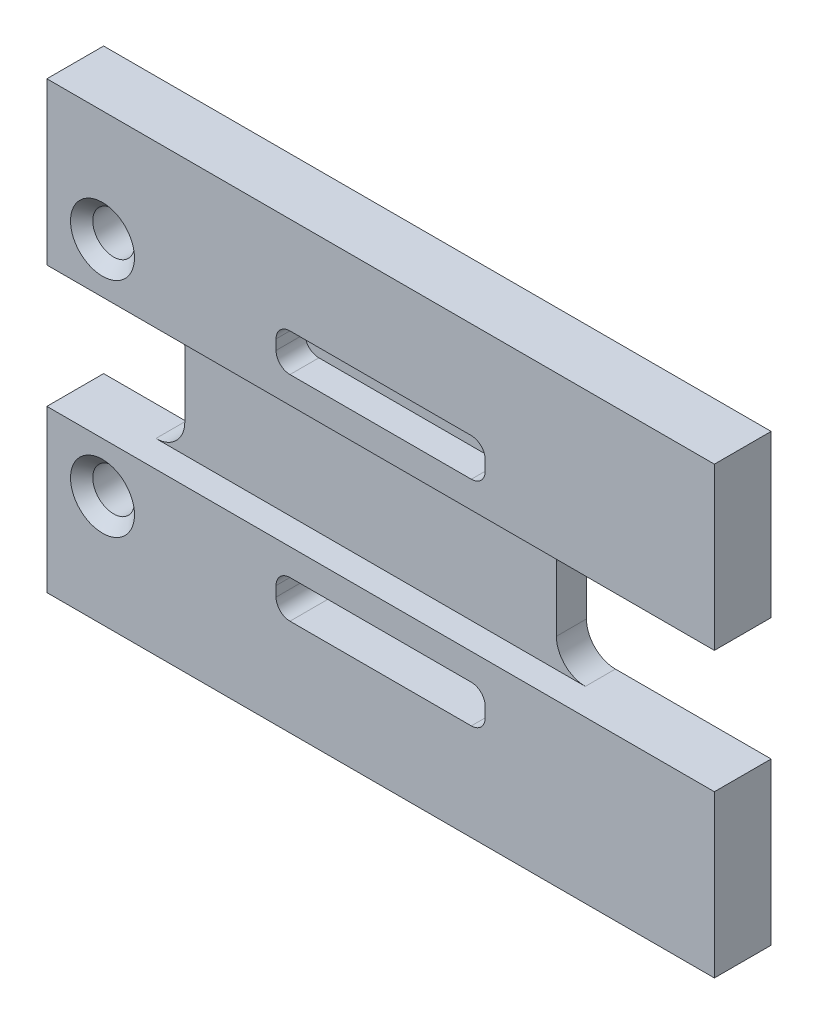
SolidWorks part; units mm, degrees
ref_plane "Front Plane" through (0, 0, 0) normal (1, 0, 0) x (0, 1, 0)
ref_plane "Top Plane" through (0, 0, 0) normal (0, 0, 1) x (0, 1, 0)
ref_plane "Right Plane" through (0, 0, 0) normal (0, 1, 0) x (-1, 0, 0)
sketch "Sketch1" plane through (0, 0, 0) normal (0, 0, 1) x (0, 1, 0)
  line L0 (-25.4, 38.1) -> (25.4, -38.1) construction
  line L1 (-25.4, 38.1) -> (25.4, 38.1)
  line L2 (-25.4, 38.1) -> (-25.4, -38.1)
  line L3 (-25.4, -38.1) -> (25.4, -38.1)
  line L4 (25.4, 38.1) -> (25.4, -38.1)
  line L5 (25.4, 38.1) -> (-25.4, -38.1) construction
  dimension "D1" = 50.8
  dimension "D2" = 76.2
extrude "Boss-Extrude1" add sketch "Sketch1" along normal blind 6.477
sketch "Sketch3" plane through (0, 0, 6.477) normal (0, 0, 1) x (1, 0, 0)
  line L0 (-38.1, 6.985) -> (38.1, 6.985)
  line L1 (-38.1, 25.4) -> (-38.1, -25.4) construction
  line L2 (38.1, -25.4) -> (38.1, 25.4) construction
  line L3 (38.1, 6.985) -> (38.1, -6.985)
  line L4 (38.1, -6.985) -> (-38.1, -6.985)
  line L5 (-38.1, -6.985) -> (-38.1, 6.985)
  line L6 (-38.1, 0) -> (0, 0) construction
  dimension "D1" = 13.97
extrude "Cut-Extrude2" cut sketch "Sketch3" against normal offset from surface (3.048 mm away) 3.429 up to face at (0, 0, 0)
sketch "Sketch2" plane through (0, 0, 6.477) normal (0, 0, 1) x (1, 0, 0)
  line L0 (-31.75, 12.7) -> (-31.75, -12.7) construction
  line L1 (-38.1, 6.985) -> (-25.4, 6.985)
  line L2 (38.1, 6.985) -> (-38.1, 6.985) construction
  line L3 (-25.4, 6.985) -> (-25.4, -6.985)
  line L4 (-38.1, -6.985) -> (38.1, -6.985) construction
  line L5 (-25.4, -6.985) -> (-38.1, -6.985)
  line L6 (-38.1, -6.985) -> (-38.1, 6.985)
  line L7 (38.1, 6.985) -> (38.1, -6.985)
  line L8 (38.1, -6.985) -> (17.018, -6.985)
  line L9 (-38.1, -6.985) -> (38.1, -6.985) construction
  line L10 (17.018, -6.985) -> (17.018, 6.985)
  line L11 (38.1, 6.985) -> (-38.1, 6.985) construction
  line L12 (17.018, 6.985) -> (38.1, 6.985)
  line L13 (-31.75, 25.4) -> (-31.75, 15.24) construction
  line L14 (38.1, 25.4) -> (-38.1, 25.4) construction
  line L15 (-31.75, 15.24) -> (38.1, 15.24) construction
  line L16 (38.1, 6.985) -> (38.1, 25.4) construction
  line L17 (-31.75, -25.4) -> (-31.75, -15.24) construction
  line L18 (-38.1, -25.4) -> (38.1, -25.4) construction
  line L19 (-31.75, -15.24) -> (38.1, -15.24) construction
  line L20 (38.1, -25.4) -> (38.1, -6.985) construction
  line L21 (-38.1, 25.4) -> (-38.1, 6.985) construction
  line L22 (0, 0) -> (-31.75, 0) construction
  circle A0 centre (-31.75, 12.7) radius 2.3813
  circle A1 centre (-31.75, -12.7) radius 2.3813
  dimension "D1" = 4.7625
  dimension "D8" = 31.75
  dimension "D2" = 25.4
  dimension "D3" = 21.082
  dimension "D4" = 12.7
  dimension "D5" = 8.255
  dimension "D6" = 6.35
extrude "Cut-Extrude1" cut sketch "Sketch2" against normal through all
fillet "Fillet1" radius 3.302 4 edges at (-25.4, -6.985, 1.7145) (-25.4, 6.985, 1.7145) (17.018, -6.985, 1.7145) (17.018, 6.985, 1.7145)
sketch "Sketch5" plane through (0, 0, 6.477) normal (0, 0, 1) x (1, 0, 0)
  line L0 (0, 11.049) -> (0, 0) construction
  line L2 (-11.938, 12.7) -> (-29.3687, 12.7) construction
  line L3 (-11.938, 14.351) -> (11.938, 14.351)
  line L4 (-11.938, 14.351) -> (-11.938, 11.049)
  line L5 (-11.938, 11.049) -> (11.938, 11.049)
  line L6 (11.938, 14.351) -> (11.938, 11.049)
  circle A0 centre (-31.75, 12.7) radius 2.3813 construction
  dimension "D2" = 3.302
  dimension "D3" = 23.876
extrude "Cut-Extrude3" cut sketch "Sketch5" against normal through all
sketch "Sketch6" plane through (0, 0, 6.477) normal (0, 0, 1) x (1, 0, 0)
  line L0 (-11.938, 11.049) -> (11.938, 11.049)
  line L1 (11.938, 11.049) -> (11.938, 10.033)
  line L2 (11.938, 10.033) -> (-11.938, 10.033)
  line L3 (-11.938, 10.033) -> (-11.938, 11.049)
  dimension "D1" = 1.016
extrude "Cut-Extrude4" cut sketch "Sketch6" against normal blind 3.302
mirror "Mirror1" about plane through (0, 0, 0) normal (0, 1, 0) of "Cut-Extrude4", "Cut-Extrude3"
fillet "Fillet4" radius 1.5875 8 edges at (-11.938, -14.351, 3.2385) (11.938, -14.351, 3.2385) (11.938, -11.049, 1.5875) (-11.938, -11.049, 1.5875) (11.938, 11.049, 1.5875) (-11.938, 11.049, 1.5875) (-11.938, 14.351, 3.2385) (11.938, 14.351, 3.2385)
fillet "Fillet5" radius 1.5875 4 edges at (-11.938, -10.033, 4.826) (11.938, -10.033, 4.826) (-11.938, 10.033, 4.826) (11.938, 10.033, 4.826)
chamfer "Chamfer1" distance 1.27 angle 45 2 edges at (-29.3687, -12.7, 6.477) (-29.3687, 12.7, 6.477)
